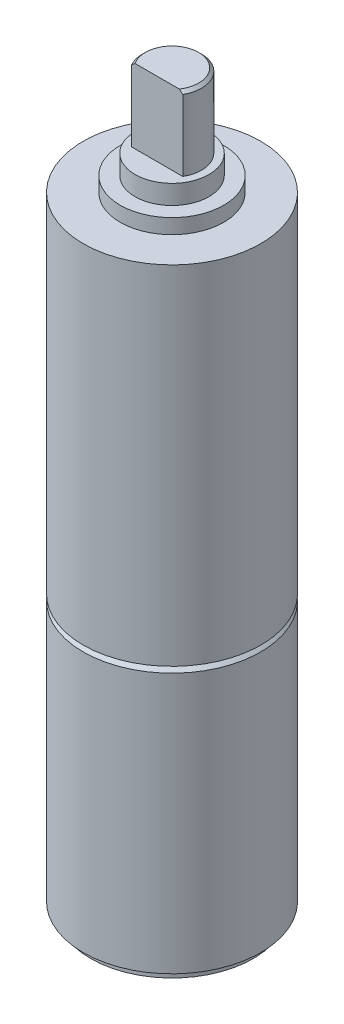
SolidWorks part; units mm, degrees
ref_plane "前视基准面" through (0, 0, 0) normal (0, 0, 1) x (1, 0, 0)
ref_plane "上视基准面" through (0, 0, 0) normal (0, 1, 0) x (1, 0, 0)
ref_plane "右视基准面" through (0, 0, 0) normal (1, 0, 0) x (0, 0, -1)
other "Configuration Table"
sketch "草图1" plane through (0, 0, 0) normal (0, 1, 0) x (1, 0, 0)
  circle A0 centre (0, 0) radius 2.75
  dimension "D1" = 5.5
extrude "凸台-拉伸1" add sketch "草图1" along normal blind 0.3
sketch "草图2" plane through (0, 0, 0) normal (0, 1, 0) x (1, 0, 0)
  circle A0 centre (0, 0) radius 3
  dimension "D1" = 6
extrude "凸台-拉伸2" add sketch "草图2" along normal blind 9 from surface at 0.3 starting at face at (0, 0.3, 2.75)
chamfer "倒角1" distance 0.2 angle 45 1 edges at (0, 9.3, 3)
sketch "草图3" plane through (0, 0, 0) normal (0, 1, 0) x (1, 0, 0)
  circle A0 centre (0, 0) radius 3
  dimension "D1" = 6
extrude "凸台-拉伸3" add sketch "草图3" along normal blind 11.75 from surface at 9.3 starting at face at (0, 9.3, 2.8)
sketch "草图4" plane through (0, 0, 0) normal (0, 1, 0) x (1, 0, 0)
  circle A0 centre (0, 0) radius 1.75
  dimension "D1" = 3.5
extrude "凸台-拉伸4" add sketch "草图4" along normal blind 0.5 from surface at 21.05 starting at face at (0, 21.05, 3)
sketch "草图5" plane through (0, 0, 0) normal (0, 1, 0) x (1, 0, 0)
  circle A0 centre (0, 0) radius 1.25
  dimension "D1" = 2.5
extrude "凸台-拉伸5" add sketch "草图5" along normal blind 1.15 from surface at 21.05 starting at face at (0, 21.05, 1.75)
sketch "草图6" plane through (0, 0, 0) normal (0, 1, 0) x (1, 0, 0)
  circle A0 centre (0, 0) radius 1
  dimension "D1" = 2
extrude "凸台-拉伸6" add sketch "草图6" along normal blind 3.65 from surface at 21.05 starting at face at (0, 21.05, 1.75)
sketch "草图7" plane through (0, 0, 0) normal (0, 1, 0) x (1, 0, 0)
  line L0 (0, -1000) -> (0, 49000) construction
  line L1 (-0.866, -0.5) -> (0.866, -0.5)
  circle A1 centre (0, 0) radius 1
  arc A2 (-0.866, -0.5) -> (0.866, -0.5) centre (0, 0) ccw
  point P9 (0, -0.5)
  dimension "D2" = 0.5
  dimension "D1" = 0
extrude "切除-拉伸1" cut sketch "草图7" against normal blind 2.5 from surface at 24.7 starting at face at (0, 24.7, 1)
chamfer "倒角2" distance 0.1 angle 45 1 edges at (0, 24.7, -1)
